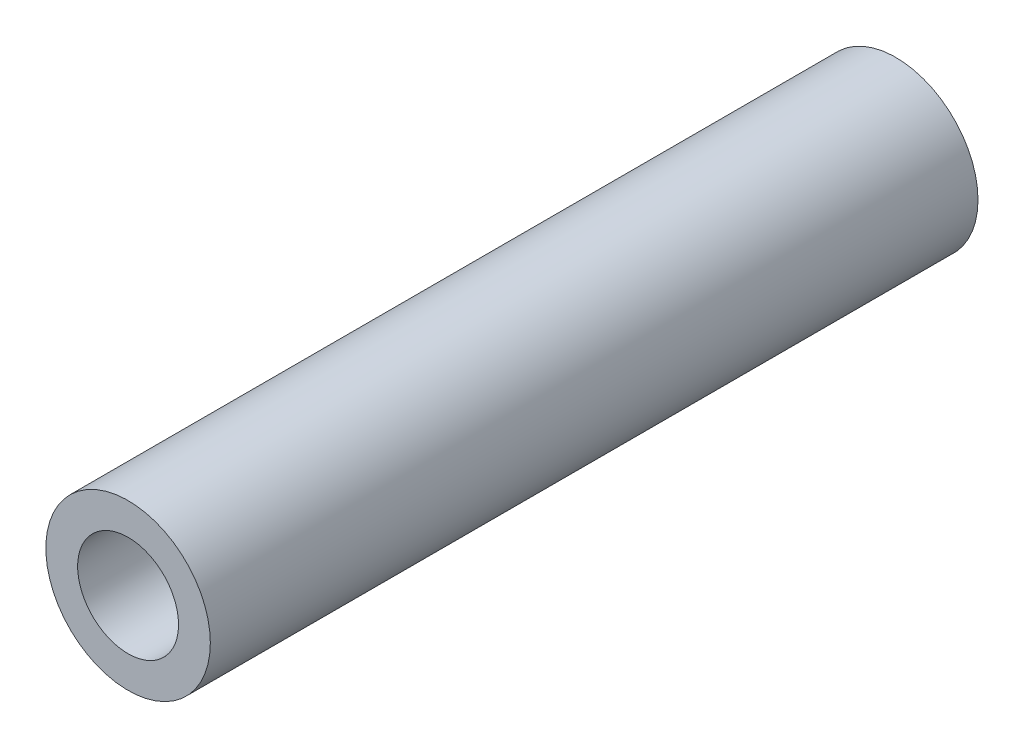
SolidWorks part; units mm, degrees
material "Nylon 101"
ref_plane "Front Plane" through (0, 0, 0) normal (0, 0, 1) x (1, 0, 0)
ref_plane "Top Plane" through (0, 0, 0) normal (0, 1, 0) x (1, 0, 0)
ref_plane "Right Plane" through (0, 0, 0) normal (1, 0, 0) x (0, 0, -1)
sketch "Sketch1" plane through (0, 0, 0) normal (0, 0, 1) x (1, 0, 0)
  circle A0 centre (0, 0) radius 2.3812
  circle A1 centre (0, 0) radius 1.4605
  dimension "OD" = 4.7625
  dimension "ID" = 2.921
extrude "Extrude1" add sketch "Sketch1" along normal mid plane 22.225
sketch "Sketch2" plane through (0, 0, 0) normal (1, 0, 0) x (0, 0, -1)
  line L0 (-11.1125, -1.4605) -> (11.1125, -1.4605) construction
  line L3 (11.1125, 1.4605) -> (-11.1125, 1.4605) construction
  line L5 (-11.1125, -1.4605) -> (11.1125, -1.4605)
  line L6 (11.1125, 1.4605) -> (-11.1125, 1.4605)
sketch "Sketch4" plane through (0, 0, 11.1125) normal (0, 0, 1) x (1, 0, 0)
  line L0 (0, 0) -> (-1.0327, 1.0327)
  line L1 (0, -2.6194) -> (0, 2.6194) construction
  circle A0 centre (0, 0) radius 1.4605 construction
  dimension "D1" = 45
